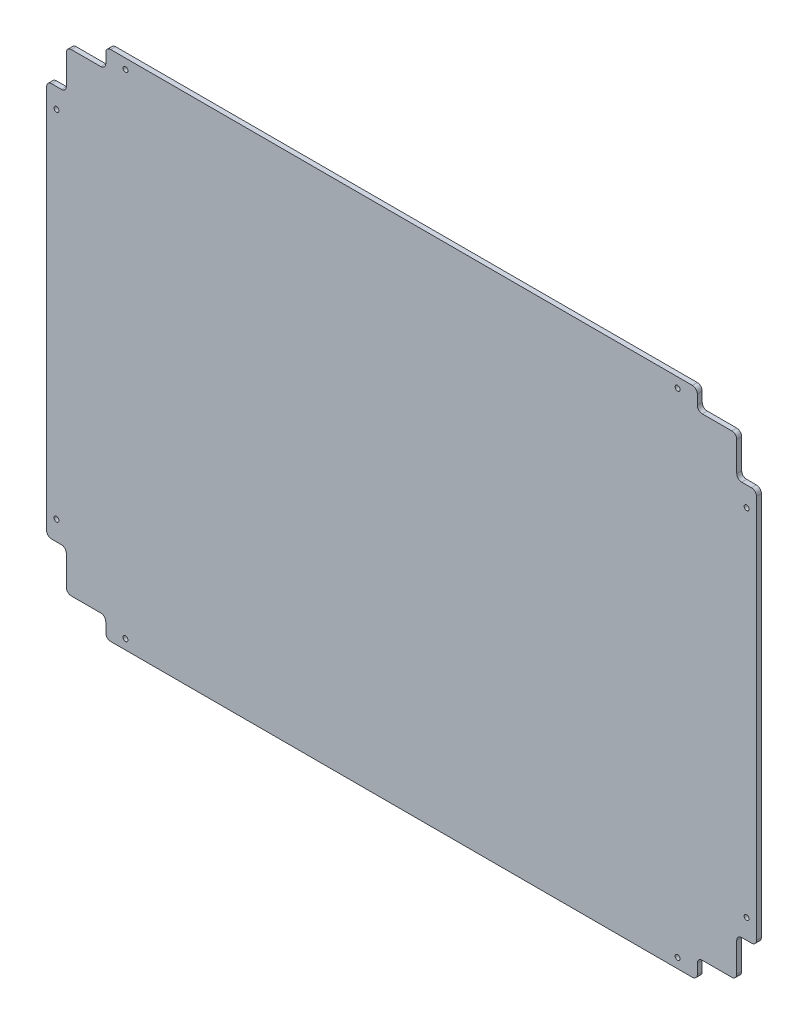
SolidWorks part; units mm, degrees
material "丙烯酸(中高冲击)"
ref_plane "前视基准面" through (0, 0, 0) normal (0, 0, 1) x (1, 0, 0)
ref_plane "上视基准面" through (0, 0, 0) normal (0, 1, 0) x (1, 0, 0)
ref_plane "右视基准面" through (0, 0, 0) normal (1, 0, 0) x (0, 0, -1)
sketch "草图1" plane through (0, 0, 0) normal (0, 0, 1) x (1, 0, 0)
  line L1 (-360, 260) -> (360, 260)
  line L2 (-360, 260) -> (-360, -260)
  line L3 (-360, -260) -> (360, -260)
  line L4 (360, 260) -> (360, -260)
  line L5 (-360, 260) -> (360, -260) construction
  line L6 (-360, -260) -> (360, 260) construction
  point P0 (0, 0)
  dimension "D1" = 720
  dimension "D2" = 520
extrude "凸台-拉伸1" add sketch "草图1" along normal blind 5
sketch "草图2" plane through (0, 0, 5) normal (0, 0, 1) x (1, 0, 0)
  line L4 (340, -240) -> (340, -200)
  line L5 (340, 240) -> (300, 240)
  line L6 (-340, 240) -> (-340, 200)
  line L7 (-340, -240) -> (-300, -240)
  line L8 (360, -260) -> (360, 260)
  line L9 (360, 260) -> (-360, 260)
  line L10 (-360, 260) -> (-360, -260)
  line L11 (-360, -260) -> (360, -260)
  line L12 (360, -260) -> (360, -200)
  line L13 (360, 260) -> (300, 260)
  line L14 (-360, 260) -> (-360, 200)
  line L15 (-360, -260) -> (-300, -260)
  line L16 (360, 200) -> (340, 200)
  line L17 (300, 260) -> (300, 240)
  line L18 (360, -200) -> (340, -200)
  line L19 (300, -240) -> (300, -260)
  line L20 (-300, -240) -> (-300, -260)
  line L21 (-340, -200) -> (-360, -200)
  line L22 (-300, 240) -> (-300, 260)
  line L23 (-340, 200) -> (-360, 200)
  line L24 (-300, 240) -> (-340, 240)
  line L25 (340, 240) -> (-340, 240) construction
  line L26 (-300, 260) -> (-360, 260)
  line L27 (360, 260) -> (-360, 260) construction
  line L28 (300, -240) -> (340, -240)
  line L29 (-340, -240) -> (340, -240) construction
  line L30 (300, -260) -> (360, -260)
  line L31 (-360, -260) -> (360, -260) construction
  line L32 (340, 200) -> (340, 240)
  line L33 (340, -240) -> (340, 240) construction
  line L34 (360, 200) -> (360, 260)
  line L35 (360, -260) -> (360, 260) construction
  line L36 (-340, -200) -> (-340, -240)
  line L37 (-340, 240) -> (-340, -240) construction
  line L38 (-360, -200) -> (-360, -260)
  line L39 (-360, 260) -> (-360, -260) construction
  dimension "D3" = 60
  dimension "D4" = 60
  dimension "D5" = 60
  dimension "D6" = 60
  dimension "D1" = 0
  dimension "D2" = 20
extrude "切除-拉伸1" cut sketch "草图2" against normal through all
sketch "草图3" plane through (0, 0, 5) normal (0, 0, 1) x (1, 0, 0)
  line L0 (360, -200) -> (360, 200) construction
  line L1 (340, 200) -> (360, 200) construction
  line L2 (300, 260) -> (300, 240) construction
  line L3 (300, 260) -> (-300, 260) construction
  line L4 (360, -200) -> (340, -200) construction
  line L5 (300, -240) -> (300, -260) construction
  line L6 (-300, -260) -> (300, -260) construction
  line L7 (-300, -260) -> (-300, -240) construction
  line L8 (-360, 200) -> (-360, -200) construction
  line L9 (-340, -200) -> (-360, -200) construction
  line L10 (-300, 240) -> (-300, 260) construction
  line L11 (-360, 200) -> (-340, 200) construction
  line L12 (-360, 200) -> (-360, -200) construction
  circle A0 centre (350, 180) radius 2.5
  circle A1 centre (280, 250) radius 2.5
  circle A2 centre (-280, 250) radius 2.5
  circle A3 centre (-350, 180) radius 2.5
  circle A4 centre (-350, -180) radius 2.5
  circle A5 centre (-280, -250) radius 2.5
  circle A6 centre (350, -180) radius 2.5
  circle A7 centre (280, -250) radius 2.5
  point P38 (-300, 250)
  dimension "D1" = 5
  dimension "D2" = 10
  dimension "D3" = 20
  dimension "D4" = 5
  dimension "D5" = 20
  dimension "D6" = 10
  dimension "D7" = 5
  dimension "D8" = 10
  dimension "D10" = 20
  dimension "D12" = 5
  dimension "D13" = 5
  dimension "D14" = 20
  dimension "D15" = 10
  dimension "D16" = 5
  dimension "D17" = 10
  dimension "D18" = 20
  dimension "D19" = 5
  dimension "D20" = 5
  dimension "D21" = 20
  dimension "D22" = 10
  dimension "D23" = 20
  dimension "D24" = 10
  dimension "D9" = 20
  dimension "D11" = 10
extrude "切除-拉伸2" cut sketch "草图3" against normal through all
fillet "圆角1" radius 5 20 edges at (300, -260, 2.5) (300, -240, 2.5) (360, -200, 2.5) (340, -240, 2.5) (340, -200, 2.5) (-300, -260, 2.5) (-300, -240, 2.5) (-340, -240, 2.5) (-340, -200, 2.5) (-360, -200, 2.5) (-360, 200, 2.5) (-340, 200, 2.5) (-340, 240, 2.5) (-300, 240, 2.5) (-300, 260, 2.5) (300, 260, 2.5) (300, 240, 2.5) (340, 240, 2.5) (340, 200, 2.5) (360, 200, 2.5)
